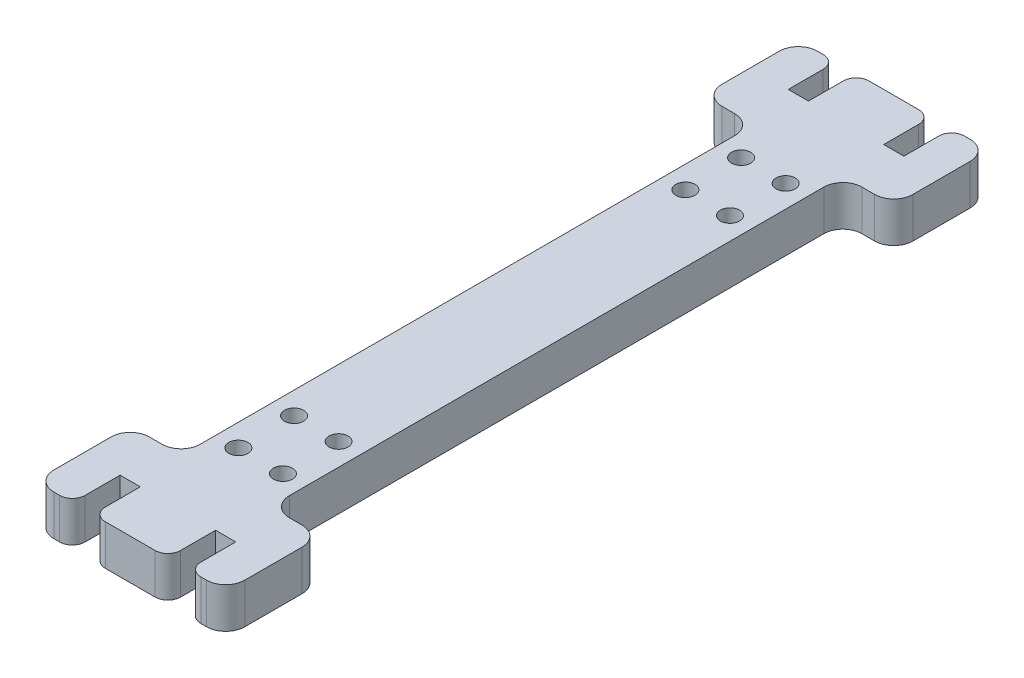
SolidWorks part; units mm, degrees
ref_plane "Front Plane" through (0, 0, 0) normal (0, 0, 1) x (1, 0, 0)
ref_plane "Top Plane" through (0, 0, 0) normal (0, 1, 0) x (1, 0, 0)
ref_plane "Right Plane" through (0, 0, 0) normal (1, 0, 0) x (0, 0, -1)
sketch "Sketch1" plane through (0, 0, 0) normal (0, 1, 0) x (1, 0, 0)
  line L0 (0, 0) -> (0, 60) construction
  line L1 (-15, 60) -> (15, 60)
  line L2 (15, 60) -> (15, 45)
  line L3 (15, 45) -> (7, 45)
  line L4 (7, 45) -> (7, -45)
  line L5 (7, 0) -> (0, 0) construction
  line L6 (-7, 45) -> (-7, -45)
  line L7 (-15, 45) -> (-7, 45)
  line L8 (-15, 60) -> (-15, 45)
  line L9 (15, -45) -> (7, -45)
  line L10 (15, -60) -> (15, -45)
  line L11 (-15, -60) -> (15, -60)
  line L12 (-15, -60) -> (-15, -45)
  line L13 (-15, -45) -> (-7, -45)
  point P17 (-7, 0)
  dimension "D1" = 60
  dimension "D2" = 7
  dimension "D3" = 15
  dimension "D4" = 15
extrude "Boss-Extrude1" add sketch "Sketch1" along normal blind 6.35
sketch "Sketch2" plane through (0, 6.35, 0) normal (0, 1, 0) x (1, 0, 0)
  line L0 (0, 60) -> (0, -60) construction
  line L1 (15, 60) -> (-15, 60) construction
  line L2 (-15, -60) -> (15, -60) construction
  line L8 (15, 45) -> (15, 60) construction
  line L9 (5.9125, 67.5) -> (9.0875, 67.5)
  line L10 (5.9125, 67.5) -> (5.9125, 52.5)
  line L11 (5.9125, 52.5) -> (9.0875, 52.5)
  line L16 (0, 0) -> (7, 0) construction
  line L17 (7, -45) -> (7, 45) construction
  line L18 (9.0875, 67.5) -> (9.0875, 52.5)
  line L19 (5.9125, 67.5) -> (9.0875, 52.5) construction
  line L24 (5.9125, 52.5) -> (9.0875, 67.5) construction
  line L25 (-5.9125, 52.5) -> (-9.0875, 67.5) construction
  line L30 (-5.9125, 67.5) -> (-9.0875, 52.5) construction
  line L31 (-9.0875, 67.5) -> (-9.0875, 52.5)
  line L32 (-5.9125, 52.5) -> (-9.0875, 52.5)
  line L33 (-5.9125, 67.5) -> (-5.9125, 52.5)
  line L34 (-5.9125, 67.5) -> (-9.0875, 67.5)
  line L35 (5.9125, -52.5) -> (9.0875, -67.5) construction
  line L36 (5.9125, -67.5) -> (9.0875, -52.5) construction
  line L37 (9.0875, -67.5) -> (9.0875, -52.5)
  line L38 (5.9125, -52.5) -> (9.0875, -52.5)
  line L39 (5.9125, -67.5) -> (5.9125, -52.5)
  line L40 (5.9125, -67.5) -> (9.0875, -67.5)
  line L41 (-5.9125, -67.5) -> (-9.0875, -52.5) construction
  line L42 (-5.9125, -52.5) -> (-9.0875, -67.5) construction
  line L43 (-5.9125, -67.5) -> (-9.0875, -67.5)
  line L44 (-5.9125, -67.5) -> (-5.9125, -52.5)
  line L45 (-5.9125, -52.5) -> (-9.0875, -52.5)
  line L46 (-9.0875, -67.5) -> (-9.0875, -52.5)
  point P6 (7.5, 60)
  point P17 (-7.5, 60)
  point P27 (7.5, -60)
  point P32 (-7.5, -60)
  point P33 (7.5, 60)
  dimension "D1" = 7.5
  dimension "D2" = 15
  dimension "D3" = 3.175
extrude "Cut-Extrude1" cut sketch "Sketch2" against normal through all
sketch "Sketch5" plane through (0, 0, 0) normal (0, -1, 0) x (1, 0, 0)
  circle A0 centre (3.5, 30.75) radius 1.5 construction
  circle A1 centre (3.5, -39.5) radius 1.5
  circle A2 centre (3.5, -39.5) radius 1.5
  circle A3 centre (-3.5, -39.5) radius 1.5
  circle A4 centre (-3.5, -39.5) radius 1.5
  circle A5 centre (-3.5, -30.75) radius 1.5
  circle A6 centre (-3.5, -30.75) radius 1.5
  circle A7 centre (-3.5, 30.75) radius 1.5 construction
  circle A8 centre (3.5, 39.5) radius 1.5 construction
  circle A9 centre (-3.5, 39.5) radius 1.5 construction
  circle A10 centre (3.5, 30.75) radius 1.5
  circle A11 centre (-3.5, 30.75) radius 1.5
  circle A12 centre (3.5, 39.5) radius 1.5
  circle A13 centre (-3.5, 39.5) radius 1.5
  circle A17 centre (3.5, -30.75) radius 1.5
  dimension "D4" = 3
  dimension "D1" = 0
  dimension "D2" = 0
  dimension "D3" = 0
extrude "Cut-Extrude2" cut sketch "Sketch5" against normal blind 10
fillet "Fillet1" radius 2 8 edges at (-5.9125, 3.175, 60) (-9.0875, 3.175, 60) (5.9125, 3.175, 60) (9.0875, 3.175, 60) (9.0875, 3.175, -60) (5.9125, 3.175, -60) (-5.9125, 3.175, -60) (-9.0875, 3.175, -60)
fillet "Fillet2" radius 3 12 edges at (-15, 3.175, 60) (-15, 3.175, 45) (-7, 3.175, 45) (15, 3.175, 60) (15, 3.175, 45) (7, 3.175, 45) (15, 3.175, -60) (15, 3.175, -45) (7, 3.175, -45) (-7, 3.175, -45) (-15, 3.175, -45) (-15, 3.175, -60)
